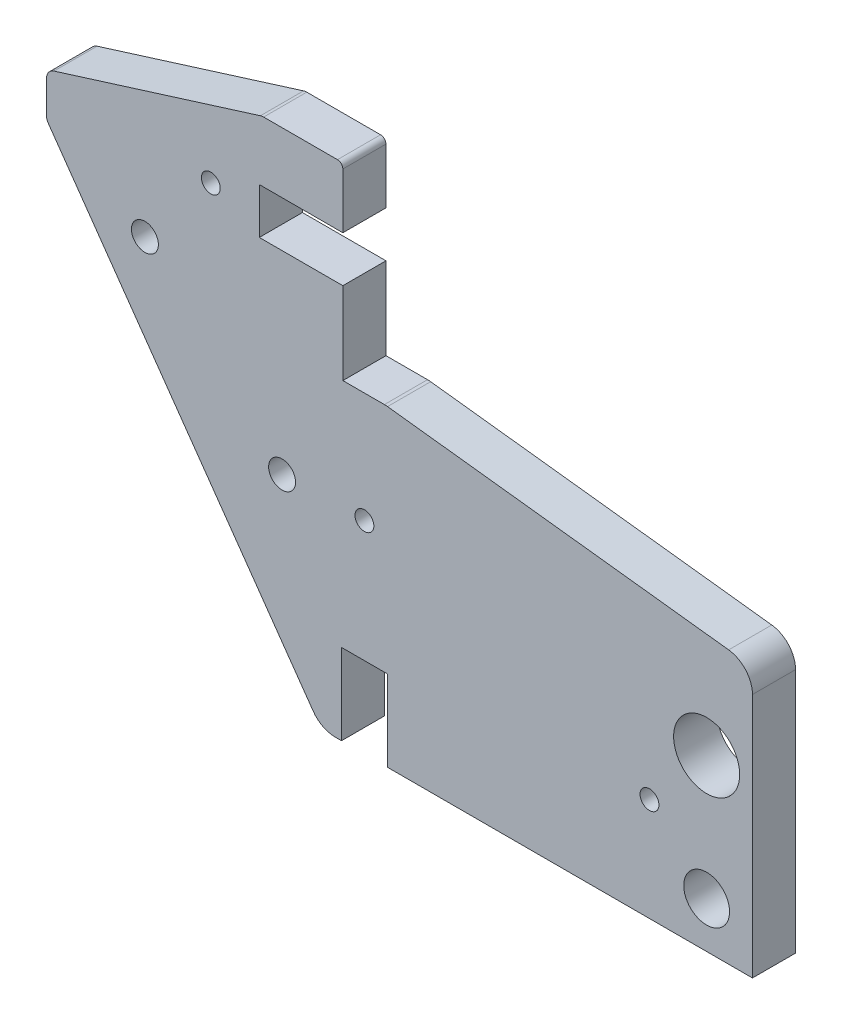
SolidWorks part; units mm, degrees
ref_plane "Front Plane" through (0, 0, 0) normal (0, 0, 1) x (1, 0, 0)
ref_plane "Top Plane" through (0, 0, 0) normal (0, 1, 0) x (1, 0, 0)
ref_plane "Right Plane" through (0, 0, 0) normal (1, 0, 0) x (0, 0, -1)
sketch "Sketch2" plane through (0, 0, 0) normal (0, 0, 1) x (1, 0, 0)
  line L0 (59.6086, 87.7801) -> (59.6086, 79.7801)
  line L1 (59.6086, 6.2801) -> (67.6086, 6.2801)
  line L3 (59.6086, 87.7801) -> (59.6086, 98.2801)
  line L4 (58.6086, 99.2801) -> (44.9138, 99.2801)
  line L5 (44.3172, 99.189) -> (6.012, 87.2187)
  line L6 (4.6086, 85.3097) -> (4.6086, 79.4131)
  line L7 (4.9727, 78.2624) -> (54.115, 8.4033)
  line L8 (58.2045, 6.2801) -> (59.6086, 6.2801)
  line L12 (67.6086, 6.2801) -> (135.6086, 6.2801)
  line L13 (135.6086, 6.2801) -> (135.6086, 51.8338)
  line L14 (131.1928, 56.7996) -> (67.8997, 64.2458)
  line L15 (67.3154, 64.2801) -> (59.6086, 64.2801)
  line L16 (59.6086, 64.2801) -> (59.6086, 79.7801)
  arc A0 (59.6086, 98.2801) -> (58.6086, 99.2801) centre (58.6086, 98.2801) ccw
  arc A1 (44.9138, 99.2801) -> (44.3172, 99.189) centre (44.9138, 97.2801) ccw
  arc A2 (6.012, 87.2187) -> (4.6086, 85.3097) centre (6.6086, 85.3097) ccw
  arc A3 (4.6086, 79.4131) -> (4.9727, 78.2624) centre (6.6086, 79.4131) ccw
  arc A4 (54.115, 8.4033) -> (58.2045, 6.2801) centre (58.2045, 11.2801) ccw
  arc A5 (135.6086, 51.8338) -> (131.1928, 56.7996) centre (130.6086, 51.8338) ccw
  arc A6 (67.8997, 64.2458) -> (67.3154, 64.2801) centre (67.3154, 59.2801) ccw
  circle A7 centre (127.1086, 37.7801) radius 6.125
  circle A8 centre (127.1086, 14.7801) radius 4.25
  circle A9 centre (116.502, 25.3867) radius 1.75
  circle A10 centre (63.6086, 43.7801) radius 1.75
  circle A11 centre (35.1086, 83.7801) radius 1.75
  dimension "D1" = 8.5
  dimension "D2" = 12.25
  dimension "D3" = 8.5
  dimension "D4" = 8.5
  dimension "D5" = 8.5
  dimension "D6" = 23
  dimension "D7" = 19.1066
extrude "Extrude1" add sketch "Sketch2" along normal blind 8
sketch "Sketch3" plane through (0, 0, 8) normal (0, 0, 1) x (1, 0, 0)
  line L0 (58.2045, 6.2801) -> (135.6086, 6.2801) construction
  line L1 (67.8586, 6.2801) -> (59.3586, 6.2801)
  line L2 (67.8586, 6.2801) -> (67.8586, 21.2801)
  line L3 (67.8586, 21.2801) -> (59.3586, 21.2801)
  line L4 (59.3586, 6.2801) -> (59.3586, 21.2801)
  line L5 (67.8586, 21.2801) -> (59.3586, 6.2801) construction
  line L6 (135.6086, 6.2801) -> (135.6086, 51.8338) construction
  line L7 (59.6086, 64.2801) -> (59.6086, 98.2801) construction
  line L8 (59.6086, 79.5301) -> (44.1086, 79.5301)
  line L9 (59.6086, 79.5301) -> (59.6086, 88.0301)
  line L10 (59.6086, 88.0301) -> (44.1086, 88.0301)
  line L11 (44.1086, 79.5301) -> (44.1086, 88.0301)
  line L12 (44.1086, 79.5301) -> (59.6086, 88.0301) construction
  line L13 (58.6086, 99.2801) -> (44.9138, 99.2801) construction
  point P6 (63.6086, 13.7801)
  point P15 (51.8586, 83.7801)
  dimension "D1" = 8.5
  dimension "D2" = 15
  dimension "D3" = 72
  dimension "D4" = 15.5
  dimension "D5" = 8.5
  dimension "D6" = 15.5
extrude "Extrude2" cut sketch "Sketch3" against normal blind 10
sketch "Sketch4" plane through (0, 0, 0) normal (0, 0, -1) x (-1, 0, 0)
  line L0 (-35.6086, 74.2801) -> (-35.6086, 38.2801) construction
  line L1 (-35.6086, 56.2801) -> (-22.8806, 69.008) construction
  line L2 (-67.8586, 6.2801) -> (-135.6086, 6.2801) construction
  line L3 (-135.6086, 6.2801) -> (-135.6086, 51.8338) construction
  line L4 (-35.6086, 56.2801) -> (-48.3365, 43.5522) construction
  circle A0 centre (-35.6086, 56.2801) radius 18
  circle A1 centre (-22.8806, 69.008) radius 2.5
  circle A2 centre (-48.3365, 43.5522) radius 2.5
  dimension "D1" = 36
  dimension "D3" = 50
  dimension "D4" = 100
  dimension "D6" = 5
  dimension "D7" = 5
  dimension "D2" = 45
  dimension "D5" = 45
extrude "Cut-Extrude1" cut sketch "Sketch4" against normal through all contours A1 | A2
